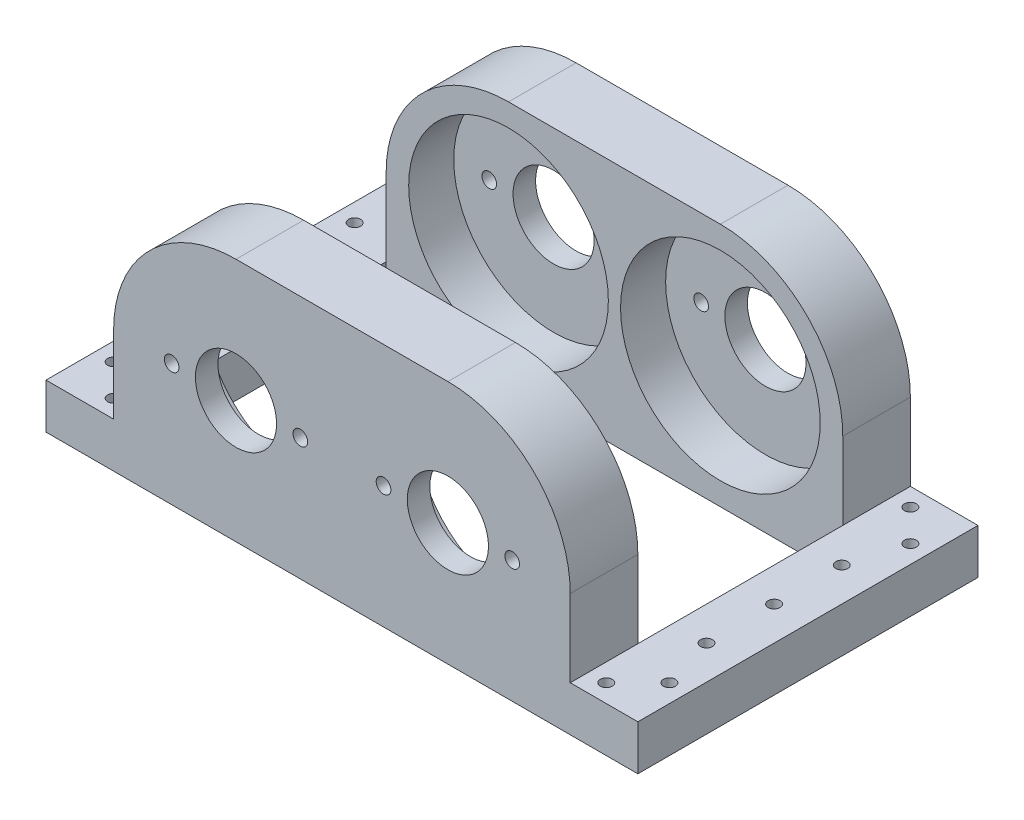
SolidWorks part; units mm, degrees
ref_plane "Front Plane" through (0, 0, 0) normal (0, 0, 1) x (1, 0, 0)
ref_plane "Top Plane" through (0, 0, 0) normal (0, 1, 0) x (1, 0, 0)
ref_plane "Right Plane" through (0, 0, 0) normal (1, 0, 0) x (0, 0, -1)
sketch "Sketch2" plane through (0, 0, 0) normal (0, 0, 1) x (1, 0, 0)
  line L0 (-47.752, 55.1612) -> (0, 55.1612)
  line L1 (27.5806, 27.5806) -> (27.5806, 10.16)
  line L2 (42.8206, 0) -> (-42.8206, 0)
  line L5 (42.8206, 0) -> (42.8206, 10.16)
  line L6 (42.8206, 10.16) -> (27.5806, 10.16)
  line L7 (-75.3326, 27.5806) -> (-75.3326, 10.16)
  line L8 (-75.3326, 10.16) -> (-90.5726, 10.16)
  line L9 (-90.5726, 10.16) -> (-90.5726, 0)
  line L10 (-90.5726, 0) -> (-42.8206, 0)
  arc A0 (27.5806, 27.5806) -> (0, 55.1612) centre (0, 27.5806) ccw
  circle A1 centre (0, 27.5806) radius 22.5006
  circle A2 centre (-47.752, 27.5806) radius 22.5006
  arc A4 (-47.752, 55.1612) -> (-75.3326, 27.5806) centre (-47.752, 27.5806) ccw
  point P10 (0, 0)
  dimension "D1" = 45.0012
  dimension "D2" = 5.08
  dimension "D8" = 45.0012
  dimension "D4" = 10.16
  dimension "D7" = 47.752
  dimension "D10" = 10.16
  dimension "D11" = 15.24
extrude "Boss-Extrude1" add sketch "Sketch2" along normal mid plane 15.24
sketch "Sketch6" plane through (0, 0, -7.62) normal (0, 0, -1) x (-1, 0, 0)
  circle A0 centre (0, 27.5806) radius 22.5006
  circle A1 centre (0, 27.5806) radius 9.144
  circle A2 centre (47.752, 27.5806) radius 22.5006
  circle A3 centre (47.752, 27.5806) radius 9.144
  dimension "D1" = 18.288
  dimension "D2" = 18.288
extrude "Boss-Extrude2" add sketch "Sketch6" against normal blind 5.08
sketch "Sketch7" plane through (0, 0, -7.62) normal (0, 0, -1) x (-1, 0, 0)
  line L0 (-14.4996, 27.5806) -> (14.4996, 27.5806)
  circle A0 centre (-14.4996, 27.5806) radius 1.651
  circle A1 centre (14.4996, 27.5806) radius 1.651
  point P5 (0, 27.5806)
  dimension "D3" = 3.302
  dimension "D4" = 3.302
  dimension "D1" = 28.9992
  dimension "D2" = 0
extrude "Cut-Extrude1" cut sketch "Sketch7" against normal blind 7.62
sketch "Sketch8" plane through (0, 0, -2.54) normal (0, 0, 1) x (1, 0, 0)
  line L0 (-62.2516, 27.5806) -> (-33.2524, 27.5806)
  circle A0 centre (-33.2524, 27.5806) radius 1.651
  circle A1 centre (-62.2516, 27.5806) radius 1.651
  circle A2 centre (-47.752, 27.5806) radius 9.144 construction
  point P7 (-47.752, 27.5806)
  dimension "D1" = 3.302
  dimension "D2" = 3.302
  dimension "D3" = 0
  dimension "D4" = 28.9992
  dimension "D5" = 0
extrude "Cut-Extrude2" cut sketch "Sketch8" against normal through all
hole_wizard "Tap Drill for #6-32 Tap1" positions "Sketch9" profile "Sketch10" hole size "#6-32" standard "ANSI Inch" end condition through all
sketch "Sketch9" plane through (0, 10.16, 0) normal (0, 1, 0) x (1, 0, 0)
  line L0 (-75.3326, -7.62) -> (-75.3326, 7.62) construction
  line L1 (-75.3326, 7.62) -> (-90.5726, 7.62) construction
  line L2 (-75.3326, -7.62) -> (-90.5726, -7.62) construction
  line L3 (-90.5726, -7.62) -> (-90.5726, 7.62) construction
  point P0 (-79.3966, 3.556)
  point P2 (-86.5086, -3.556)
  point P18 (0, 0)
  point P19 (0, 0)
  dimension "D1" = 4.064
  dimension "D2" = 4.064
  dimension "D3" = 4.064
  dimension "D4" = 4.064
sketch "Sketch10" plane through (-79.3966, 10.16, -3.556) normal (1, 0, 0) x (0, 0, 1)
  line L0 (0, 0) -> (0, 10.16)
  line L1 (0, 10.16) -> (1.3525, 10.16)
  line L2 (1.3525, 10.16) -> (1.3525, 0)
  line L5 (1.3525, 0) -> (0, 0)
  line L11 (0, -6.35) -> (0, 107.95) construction
  dimension "Thru Hole Dia." = 2.7051
  dimension "Thru Hole Depth" = 10.16
ref_plane "Plane1" through (-23.876, 0, 0) normal (-1, 0, 0) x (0, 0, 1)
mirror "Mirror1" about plane through (-23.876, 0, 0) normal (-1, 0, 0) of "Tap Drill for #6-32 Tap1"
ref_plane "Plane2" through (0, 0, 30.7099) normal (0, 0, 1) x (1, 0, 0)
sketch "Sketch11" plane through (0, 0, 7.62) normal (0, 0, 1) x (1, 0, 0)
  line L0 (-90.5726, 0) -> (42.8206, 0) construction
  line L1 (-90.5726, 10.16) -> (-75.3326, 10.16)
  line L2 (-90.5726, 10.16) -> (-90.5726, 0)
  line L3 (-90.5726, 0) -> (-75.3326, 0)
  line L4 (-75.3326, 10.16) -> (-75.3326, 0)
  line L6 (27.5806, 10.16) -> (42.8206, 10.16)
  line L7 (27.5806, 10.16) -> (27.5806, 0)
  line L8 (27.5806, 0) -> (42.8206, 0)
  line L9 (42.8206, 10.16) -> (42.8206, 0)
  dimension "D1" = 15.24
extrude "Boss-Extrude3" add sketch "Sketch11" along normal blind 23.0899
mirror "Mirror5" about plane through (0, 0, 30.7099) normal (0, 0, 1) of bodies 111
hole_wizard "Tap Drill for #6-32 Tap2" positions "Sketch12" profile "Sketch13" hole size "#6-32" standard "ANSI Inch" end condition through all
sketch "Sketch12" plane through (0, 10.16, 0) normal (0, 1, 0) x (1, 0, 0)
  line L1 (-82.9526, -30.7099) -> (-82.9526, -15.4699)
  line L3 (-82.9526, -30.7099) -> (-82.9526, -45.9499)
  line L5 (-90.5726, -69.0397) -> (-90.5726, 7.62) construction
  line L6 (-30.3386, -30.7099) -> (30.3386, -30.7099) construction
  point P0 (-82.9526, -30.7099)
  point P2 (-82.9526, -45.9499)
  point P4 (-82.9526, -15.4699)
  dimension "D1" = 7.62
  dimension "D2" = 0
  dimension "D3" = 15.24
  dimension "D4" = 15.24
sketch "Sketch13" plane through (-82.9526, 10.16, 30.7099) normal (1, 0, 0) x (0, 0, 1)
  line L0 (0, 0) -> (0, 10.16)
  line L1 (0, 10.16) -> (1.3525, 10.16)
  line L2 (1.3525, 10.16) -> (1.3525, 0)
  line L5 (1.3525, 0) -> (0, 0)
  line L11 (0, -6.35) -> (0, 107.95) construction
  dimension "Thru Hole Dia." = 2.7051
  dimension "Thru Hole Depth" = 10.16
ref_plane "Plane3" through (-23.876, 0, 0) normal (-1, 0, 0) x (0, 0, 1)
mirror "Mirror6" about plane through (-23.876, 0, 0) normal (-1, 0, 0) of "Tap Drill for #6-32 Tap2"
